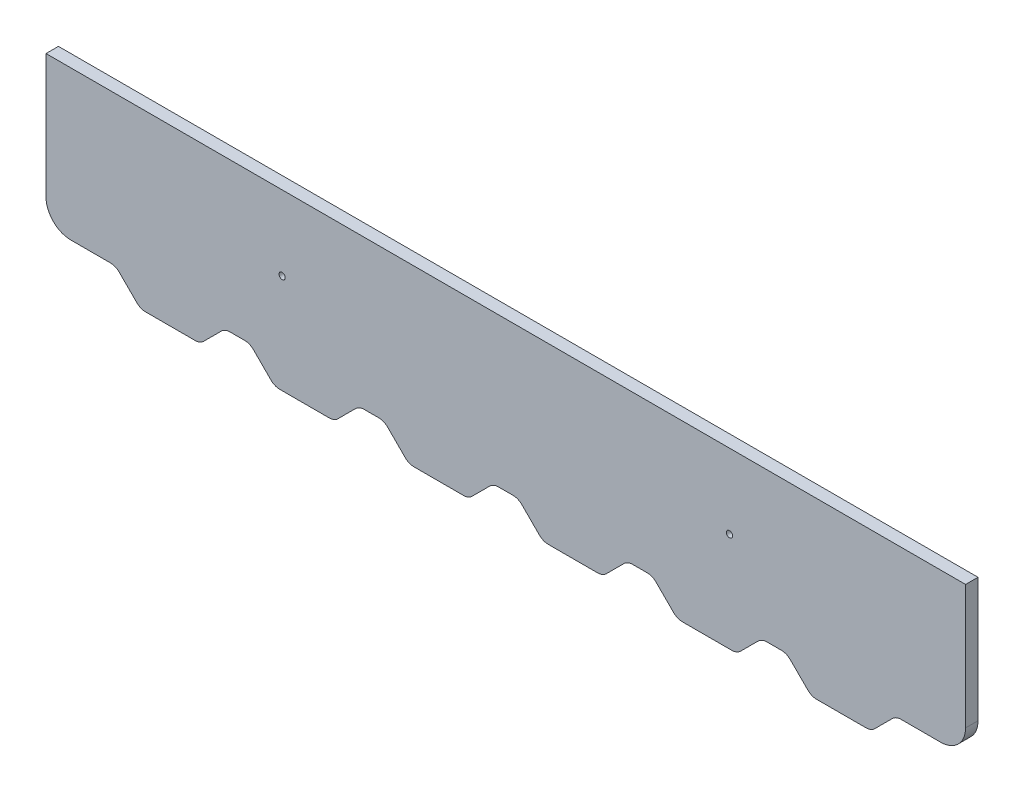
SolidWorks part; units mm, degrees
ref_plane "Front Plane" through (0, 0, 0) normal (0, 0, 1) x (1, 0, 0)
ref_plane "Top Plane" through (0, 0, 0) normal (0, 1, 0) x (1, 0, 0)
ref_plane "Right Plane" through (0, 0, 0) normal (1, 0, 0) x (0, 0, -1)
sketch "Sketch1" plane through (0, 0, 0) normal (0, 0, 1) x (1, 0, 0)
  line L0 (0, 0) -> (0, -30) construction
  line L1 (-185, -30) -> (-157, -30)
  line L2 (-185, -30) -> (-185, 30)
  line L3 (-185, 30) -> (185, 30)
  line L4 (185, -30) -> (185, 30)
  line L5 (-185, -30) -> (185, 30) construction
  line L6 (-185, 30) -> (185, -30) construction
  line L7 (0, 0) -> (-185, 0) construction
  line L8 (-54, -30) -> (-54, -40) construction
  line L9 (-108, -30) -> (-108, -45.8071) construction
  line L10 (-5, -30) -> (-15, -40)
  line L11 (-15, -40) -> (-39, -40)
  line L12 (-39, -40) -> (-49, -30)
  line L13 (-69, -40) -> (-59, -30)
  line L14 (-103, -30) -> (-93, -40)
  line L15 (-93, -40) -> (-69, -40)
  line L16 (-147, -40) -> (-157, -30)
  line L17 (-123, -40) -> (-147, -40)
  line L18 (-113, -30) -> (-123, -40)
  line L19 (5, -30) -> (15, -40)
  line L20 (15, -40) -> (39, -40)
  line L21 (39, -40) -> (49, -30)
  line L22 (69, -40) -> (59, -30)
  line L23 (93, -40) -> (69, -40)
  line L24 (103, -30) -> (93, -40)
  line L25 (113, -30) -> (123, -40)
  line L26 (123, -40) -> (147, -40)
  line L27 (147, -40) -> (157, -30)
  line L28 (-113, -30) -> (-103, -30)
  line L29 (-59, -30) -> (-49, -30)
  line L30 (-5, -30) -> (5, -30)
  line L31 (49, -30) -> (59, -30)
  line L32 (103, -30) -> (113, -30)
  line L33 (157, -30) -> (185, -30)
  circle A0 centre (-90, 0) radius 1.25
  circle A1 centre (90, 0) radius 1.25
  point P0 (0, 0)
  dimension "D3" = 2.5
  dimension "D4" = 90
  dimension "D1" = 370
  dimension "D2" = 60
  dimension "D5" = 54
  dimension "D6" = 54
  dimension "D7" = 10
  dimension "D8" = 135
  dimension "D9" = 5
  dimension "D10" = 5
  dimension "D11" = 135
  dimension "D12" = 10
extrude "Boss-Extrude1" add sketch "Sketch1" along normal blind 5
fillet "Fillet1" radius 5 24 edges at (103, -30, 2.5) (113, -30, 2.5) (123, -40, 2.5) (147, -40, 2.5) (157, -30, 2.5) (93, -40, 2.5) (69, -40, 2.5) (59, -30, 2.5) (49, -30, 2.5) (39, -40, 2.5) (-59, -30, 2.5) (-49, -30, 2.5) (-39, -40, 2.5) (-15, -40, 2.5) (-5, -30, 2.5) (5, -30, 2.5) (15, -40, 2.5) (-69, -40, 2.5) (-93, -40, 2.5) (-103, -30, 2.5) (-113, -30, 2.5) (-123, -40, 2.5) (-147, -40, 2.5) (-157, -30, 2.5)
fillet "Fillet2" radius 10 2 edges at (185, -30, 2.5) (-185, -30, 2.5)
